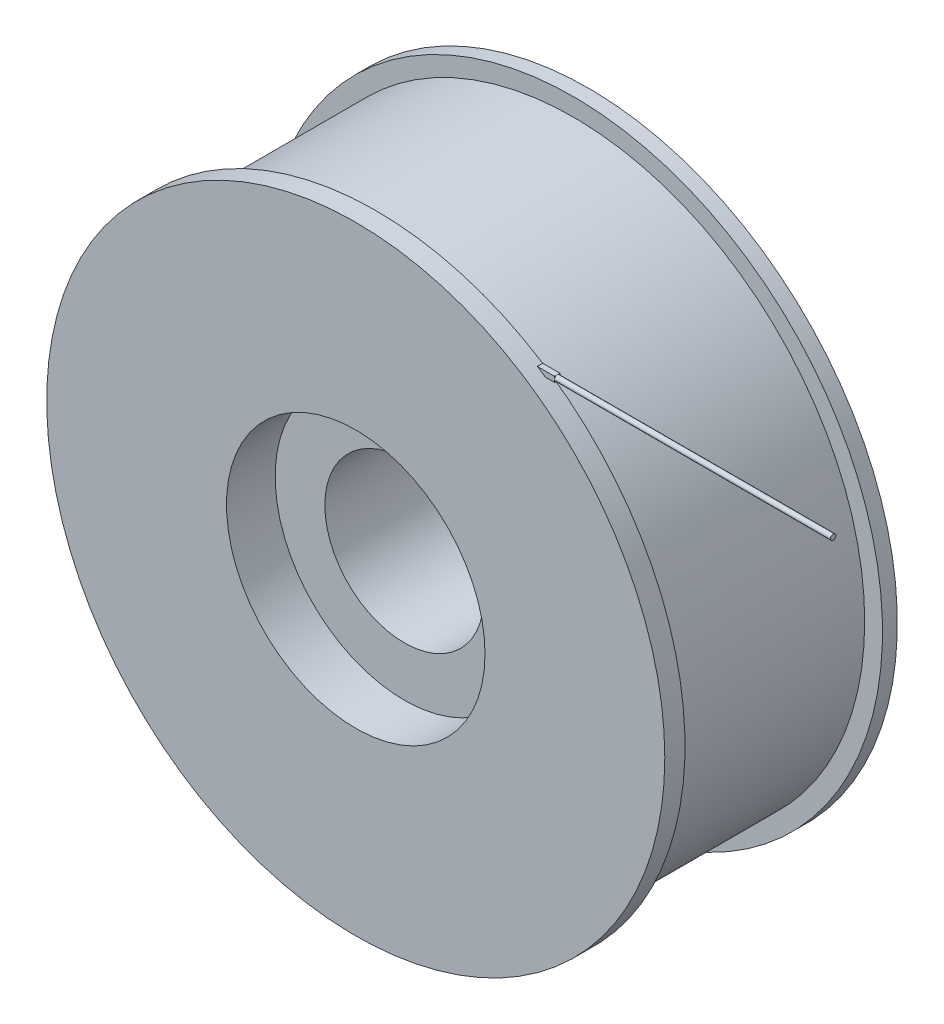
SolidWorks part; units mm, degrees
ref_plane "Front Plane" through (0, 0, 0) normal (0, 0, 1) x (1, 0, 0)
ref_plane "Top Plane" through (0, 0, 0) normal (0, 1, 0) x (1, 0, 0)
ref_plane "Right Plane" through (0, 0, 0) normal (1, 0, 0) x (0, 0, -1)
sketch "Sketch1" plane through (0, 0, 0) normal (0, 0, 1) x (1, 0, 0)
  circle A0 centre (0, 0) radius 100.8
  circle A1 centre (0, 0) radius 25.95
  dimension "D1" = 201.6
  dimension "D2" = 51.9
extrude "Boss-Extrude1" add sketch "Sketch1" along normal blind 4.84
sketch "Sketch2" plane through (0, 0, 4.84) normal (0, 0, 1) x (1, 0, 0)
  circle A0 centre (0, 0) radius 25.95
  circle A1 centre (0, 0) radius 45.11
  circle A2 centre (0, 0) radius 25.95 construction
  dimension "D1" = 90.22
extrude "Boss-Extrude2" add sketch "Sketch2" along normal blind 66.17
sketch "Sketch3" plane through (0, 0, 71.01) normal (0, 0, 1) x (1, 0, 0)
  circle A0 centre (0, 0) radius 25.95 construction
  circle A1 centre (0, 0) radius 25.95
  circle A2 centre (0, 0) radius 100.8
  circle A3 centre (0, 0) radius 100.8 construction
extrude "Boss-Extrude3" add sketch "Sketch3" along normal blind 4.84
sketch "Sketch4" plane through (0, 0, 75.85) normal (0, 0, 1) x (1, 0, 0)
  circle A0 centre (0, 0) radius 42.16
  dimension "D1" = 84.32
extrude "Cut-Extrude1" cut sketch "Sketch4" against normal blind 15.86
sketch "Sketch5" plane through (0, 0, 71.01) normal (0, 0, -1) x (-1, 0, 0)
  circle A1 centre (0, 0) radius 100.8
  circle A2 centre (0, 0) radius 100.8
  circle A3 centre (0, 0) radius 45.11
  circle A4 centre (0, 0) radius 45.11
  circle A9 centre (0, 0) radius 95
  circle M4 centre (0, 0) radius 45.11
  dimension "D3" = 190
  dimension "D1" = 0
  dimension "D2" = 0
extrude "Boss-Extrude4" add sketch "Sketch5" along normal up to surface (66.17 mm away) contours A9 M4 up to face at (100.8, 0, 4.84)
sketch "Sketch8" plane through (0, 0, 71.01) normal (0, 0, -1) x (-1, 0, 0)
  line L0 (0, 0) -> (-156.1787, 0) construction
  line L1 (-40, 84.87) -> (-40, 83.12)
  line L4 (-40, 84.87) -> (0, 84.87)
  line L6 (-40, 83.12) -> (-18.1504, 83.12)
  line L11 (-18.1504, 83.12) -> (0, 84.87)
  line L12 (-150, 84.87) -> (-150, 83.12)
  line L13 (-40, 84.87) -> (-150, 84.87)
  line L14 (-40, 83.12) -> (-150, 83.12)
  circle A1 centre (0, 0) radius 100.8
  circle A2 centre (0, 0) radius 100.8
  dimension "D1" = 0
extrude "Boss-Extrude6" add sketch "Sketch8" along normal blind 1.75
sketch "Sketch9" plane through (150, 0, 0) normal (1, 0, 0) x (0, 0, -1)
  line L1 (-71.1086, 84.9745) -> (-69.1614, 84.9745)
  line L2 (-71.1086, 84.9745) -> (-71.1086, 83.0155)
  line L3 (-69.26, 83.12) -> (-69.26, 84.87)
  line L4 (-71.1086, 83.0155) -> (-69.1614, 83.0155)
  line L5 (-69.1614, 84.9745) -> (-69.1614, 83.0155)
  circle A0 centre (-70.135, 83.995) radius 0.875
  line M1 (-71.01, 84.87) -> (-71.01, 83.12)
  line M2 (-71.01, 83.12) -> (-69.26, 83.12)
  line M3 (-69.26, 83.12) -> (-69.26, 84.87)
  line M4 (-69.26, 84.87) -> (-71.01, 84.87)
extrude "Cut-Extrude6" cut sketch "Sketch9" against normal blind 90 contours L5 L1 L2 L4 L3 M1 M4 M3 M2 | A0 M1 M2 | A0 M2 M3 | A0 L3 M4 | A0 M4 M1
